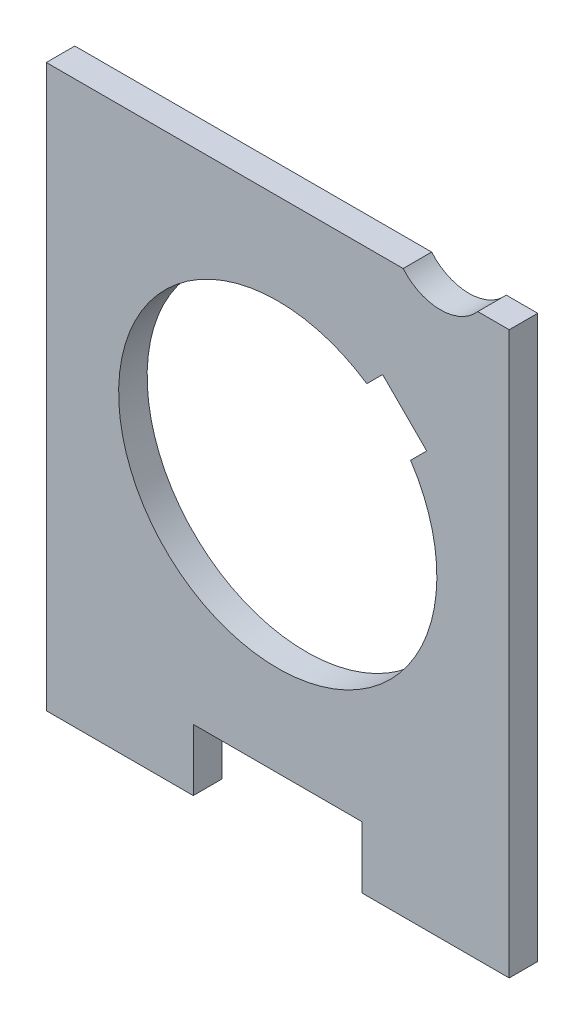
SolidWorks part; units mm, degrees
ref_plane "Front Plane" through (0, 0, 0) normal (0, 0, 1) x (1, 0, 0)
ref_plane "Top Plane" through (0, 0, 0) normal (0, 1, 0) x (1, 0, 0)
ref_plane "Right Plane" through (0, 0, 0) normal (1, 0, 0) x (0, 0, -1)
sketch "Sketch1" plane through (0, 0, 0) normal (0, 0, 1) x (1, 0, 0)
  line L1 (0, 0) -> (40, 0)
  line L2 (0, 0) -> (0, 43.18)
  line L3 (0, 43.18) -> (40, 43.18)
  line L4 (40, 0) -> (40, 43.18)
  dimension "D1" = 40
  dimension "D2" = 43.18
extrude "Base" add sketch "Sketch1" along normal blind 2.4638
sketch "Sketch2" plane through (0, 0, 0) normal (0, -1, 0) x (1, 0, 0)
  line L0 (0, 2.4638) -> (40, 2.4638) construction
  line L1 (0, 0) -> (12.7, 0)
  line L2 (0, 0) -> (0, 2.4638)
  line L3 (0, 2.4638) -> (12.7, 2.4638)
  line L4 (12.7, 0) -> (12.7, 2.4638)
  line L5 (12.7, 1.2319) -> (27.3, 1.2319) construction
  line L6 (40, 0) -> (27.3, 0)
  line L7 (40, 0) -> (40, 2.4638)
  line L8 (40, 2.4638) -> (27.3, 2.4638)
  line L9 (27.3, 0) -> (27.3, 2.4638)
  dimension "D1" = 12.7
extrude "Bottom Tabs" add sketch "Sketch2" along normal blind 5.334
sketch "Sketch4" plane through (0, 0, 2.4638) normal (0, 0, 1) x (1, 0, 0)
  line L3 (31.482, 29.1548) -> (32.8715, 30.5443)
  line L4 (32.8715, 30.5443) -> (29.0614, 34.3545)
  line L5 (29.0614, 34.3545) -> (27.6932, 32.9863)
  line L6 (31.482, 29.1548) -> (32.8715, 30.5443)
  line L7 (32.8715, 30.5443) -> (29.0614, 34.3545)
  line L8 (29.0614, 34.3545) -> (27.6932, 32.9863)
  arc A1 (27.6932, 32.9863) -> (31.482, 29.1548) centre (20, 21.59) ccw construction
  arc A2 (27.6932, 32.9863) -> (31.482, 29.1548) centre (20, 21.59) ccw
  arc A4 (31.482, 29.1548) -> (27.6932, 32.9863) centre (20, 21.59) ccw
  dimension "D1" = 0
extrude "Mount Points" cut sketch "Sketch4" against normal through all
extrude "Cut-Extrude2" cut sketch "Sketch6" against normal through all
sketch "Sketch6" plane through (18.2464, 22.2936, 55.7276) normal (0, 0, 1) x (1, 0, 0)
  circle A2 centre (15.8136, 23.6491) radius 2.975 construction
  circle A3 centre (15.8136, 23.6491) radius 4.245
equation "\"material\"= \"acrylic_sm@base.assembly\""
equation "\"D1@Base\"=\"material\""
equation "\"D1@Bottom Tabs\"=\"mdf@base.assembly\""
